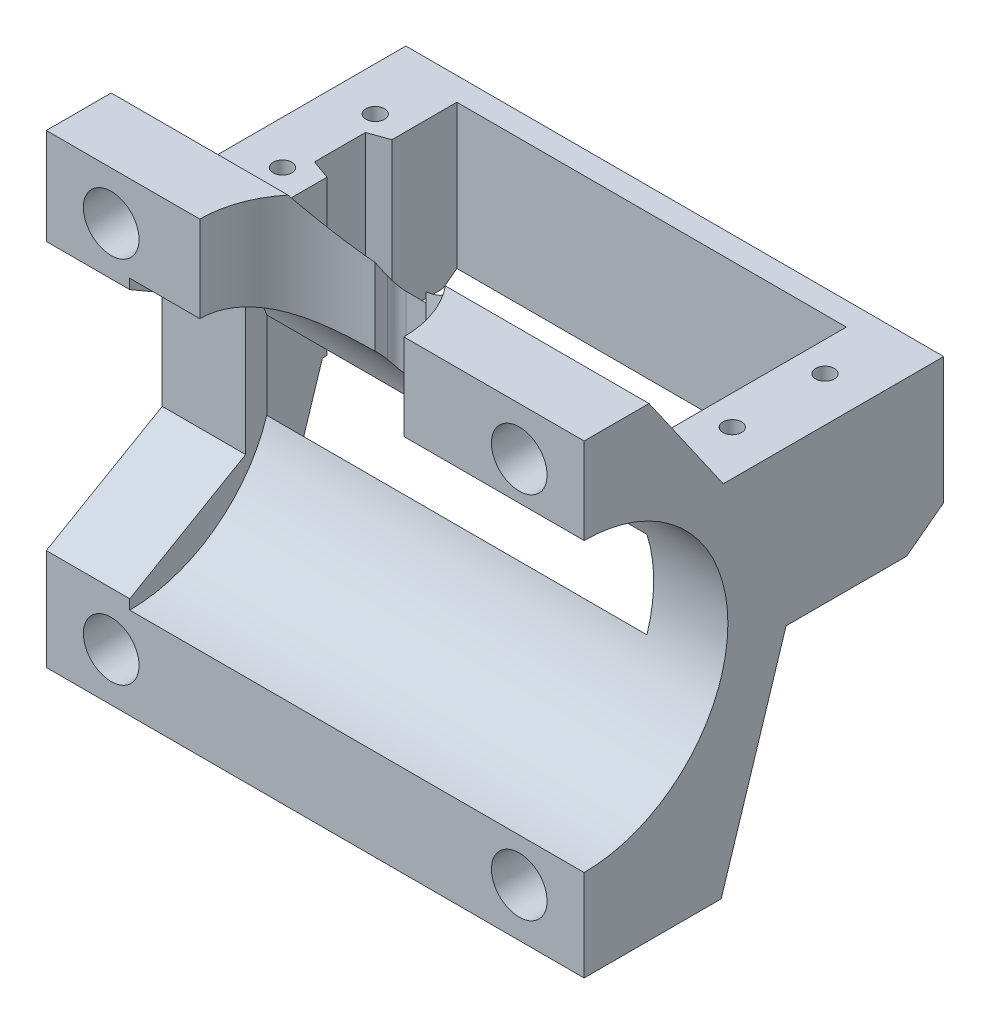
SolidWorks part; units mm, degrees
ref_plane "Front Plane" through (0, 0, 0) normal (0, 0, 1) x (1, 0, 0)
ref_plane "Top Plane" through (0, 0, 0) normal (0, 1, 0) x (1, 0, 0)
ref_plane "Right Plane" through (0, 0, 0) normal (1, 0, 0) x (0, 0, -1)
ref_plane "Plane1" through (0, -30, 0) normal (0, 1, 0) x (1, 0, 0)
sketch "Sketch1" plane through (0, -30, 0) normal (0, 1, 0) x (1, 0, 0)
  line L0 (-4.2598, -25.7738) -> (4.15, -25.7738) construction
  line L1 (29, -25.7738) -> (-29, -25.7738)
  line L2 (29, -25.7738) -> (29, 13)
  line L3 (29, 13) -> (-29, 13)
  line L4 (-29, -25.7738) -> (-29, 13)
  line L5 (29, -25.7738) -> (-29, 13) construction
  line L6 (29, 13) -> (-29, -25.7738) construction
  line L8 (27, 3.8) -> (27, -3.8) construction
  line L9 (-8.46, 10) -> (19.75, 10) construction
  line L10 (-27, -3.8) -> (-27, 3.8) construction
  line L12 (21, 10.5) -> (-21, 10.5)
  line L13 (21, 10.5) -> (21, -11)
  line L14 (21, -11) -> (-21, -11)
  line L15 (-21, 10.5) -> (-21, -11)
  point P0 (0, -6.3869)
  point P9 (-0.0549, -25.7738)
  dimension "D1" = 2
  dimension "D2" = 2.5
  dimension "D3" = 2
  dimension "D4" = 3
  dimension "D5" = 8
  dimension "D6" = 8
  dimension "D7" = 21.5
extrude "Boss-Extrude2" add sketch "Sketch1" along normal up to surface (38.65 mm away)
sketch "Sketch6" plane through (29, 0, 0) normal (1, 0, 0) x (0, 0, -1)
  line L0 (-11, -30) -> (-4, -8)
  line L1 (-25.7738, -30) -> (13, -30) construction
  line L2 (-4, -8) -> (9, -8)
  line L3 (9, -8) -> (13, -5)
  line L4 (13, 8.65) -> (13, -30) construction
  line L5 (13, -5) -> (13, -30)
  line L6 (13, -30) -> (-11, -30)
  dimension "D1" = 24
  dimension "D2" = 17
  dimension "D3" = 22
  dimension "D4" = 3
  dimension "D5" = 4
extrude "Cut-Extrude3" cut sketch "Sketch6" against normal through all
sketch "Sketch7" plane through (0, -8, 0) normal (0, -1, 0) x (1, 0, 0)
  line L0 (-21, -9) -> (-21, 4) construction
  line L1 (-21, -9) -> (-29, -9)
  line L2 (-21, -9) -> (-21, 4)
  line L3 (-21, 4) -> (-29, 4)
  line L4 (-29, -9) -> (-29, 4)
  line L5 (-29, 4) -> (-29, 11) construction
  line L6 (-29, -9) -> (-21, -9) construction
  line L7 (-29, 4) -> (-21, 4) construction
extrude "Cut-Extrude4" [suppressed] cut sketch "Sketch7" against normal blind 8
sketch "Sketch8" plane through (-29, 0, 0) normal (-1, 0, 0) x (0, 0, 1)
  line L0 (25.7738, 8.65) -> (25.7738, -30) construction
  line L1 (25.7738, 9.7838) -> (13.2738, 2.5669)
  line L2 (13.2738, 2.5669) -> (13.2738, -11.8669)
  line L3 (13.2738, -11.8669) -> (25.7738, -19.0838)
  line L4 (25.7738, -19.0838) -> (38.2738, -11.8669)
  line L5 (38.2738, -11.8669) -> (38.2738, 2.5669)
  line L6 (38.2738, 2.5669) -> (25.7738, 9.7838)
  circle A0 centre (25.7738, -4.65) radius 12.5 construction
  dimension "D1" = 12.5
sketch "Sketch9" plane through (-29, 0, 0) normal (-1, 0, 0) x (0, 0, 1)
  line L0 (10.7738, 8.65) -> (18.7738, 20.15)
  line L1 (25.7738, 8.65) -> (-13, 8.65) construction
  line L2 (18.7738, 20.15) -> (25.7738, 20.15)
  line L3 (25.7738, 20.15) -> (25.7738, 8.65)
  line L4 (10.7738, 8.65) -> (25.7738, 8.65)
  dimension "D1" = 7
  dimension "D2" = 11.5
  dimension "D3" = 15
extrude "Boss-Extrude3" add sketch "Sketch9" against normal up to surface (58 mm away) up to face at (29, -9.1, 4.5068)
extrude "Cut-Extrude5" cut sketch "Sketch8" against normal through all
sketch "Sketch10" plane through (0, 20.15, 0) normal (0, 1, 0) x (1, 0, 0)
  line L0 (29, -25.7738) -> (-29, -25.7738) construction
  line L1 (-4.2, -25.7738) -> (1.3, -25.7738)
  line L2 (-4.2, -25.7738) -> (-4.2, -12.7738)
  line L3 (-4.2, -12.7738) -> (1.3, -12.7738)
  line L4 (1.3, -25.7738) -> (1.3, -12.7738)
  circle A0 centre (-1.45, -25.7738) radius 11
  arc A1 (-7.95, -25.7738) -> (5.05, -25.7738) centre (-1.45, -25.7738) ccw construction
  point P11 (-1.45, -12.7738)
  line M7 (29, -18.7738) -> (-29, -18.7738)
  line M9 (-29, -25.7738) -> (29, -25.7738)
  dimension "D1" = 22
  dimension "D2" = 5.5
  dimension "D3" = 13
extrude "Cut-Extrude6" cut sketch "Sketch10" against normal blind 17 contours A0 L4 L3 L2 | A0 L4 M9 M7 | A0 L4 M7 | L4 A0 L2 M7 | A0 L2 M7 M9 | L4 L2 M9 M7 | L2 A0 M7
fillet "Fillet1" radius 1 2 edges at (1.3, 7.3375, 12.7738) (-4.2, 7.3375, 12.7738)
sketch "Sketch11" plane through (0, 0, 0) normal (1, 0, 0) x (0, 0, -1)
  circle A0 centre (-25.7738, -4.65) radius 15.5
  dimension "D1" = 31
extrude "Cut-Extrude7" cut sketch "Sketch11" against normal blind 20 and the other way through all contours A0
sketch "Sketch12" plane through (0, 0, 25.7738) normal (0, 0, 1) x (1, 0, 0)
  line L0 (-29, -4.925) -> (29, -4.925) construction
  line L1 (-29, 20.15) -> (-29, 9.7838) construction
  line L2 (29, 20.15) -> (29, 10.85) construction
  line L3 (-29, -30) -> (29, -30) construction
  line L4 (29, 20.15) -> (9.55, 20.15) construction
  circle A0 centre (-22, 14.9669) radius 3
  circle A1 centre (22, 14.9669) radius 3
  circle A2 centre (22, -24.8169) radius 3
  circle A3 centre (-22, -24.8169) radius 3
  point P14 (-29, 14.9669)
  dimension "D1" = 6
  dimension "D2" = 7
  dimension "D3" = 7
extrude "Cut-Extrude8" cut sketch "Sketch12" against normal blind 20
sketch "Sketch13" plane through (0, 0, 0) normal (0, 0, 1) x (1, 0, 0)
  line L0 (-29, -4.925) -> (29, -4.925) construction
  line L1 (29, 8.65) -> (29, -5) construction
  line L2 (-29, 8.65) -> (-29, -5) construction
  line L3 (29, 20.15) -> (7.0353, 20.15) construction
  line L4 (-21, -30) -> (21, -30) construction
  circle A0 centre (22, 14.9669) radius 4
  circle A1 centre (-22, 14.9669) radius 4
  circle A2 centre (22, -24.8169) radius 4
  circle A3 centre (-22, -24.8169) radius 4
  dimension "D1" = 8
extrude "Cut-Extrude9" cut sketch "Sketch13" along normal blind 20
sketch "Sketch15" plane through (0, 8.65, 0) normal (0, 1, 0) x (1, 0, 0)
  line L0 (29, 13) -> (29, -10.7738) construction
  line L1 (-29, 0) -> (29, 0) construction
  line L2 (-29, -10.7738) -> (-29, 13) construction
  circle A0 centre (-24.3, 5) radius 1
  circle A1 centre (-24.3, -5) radius 1
  circle A2 centre (24.2, 5) radius 1
  circle A3 centre (24.2, -5) radius 1
  dimension "D1" = 2
  dimension "D2" = 2
  dimension "D3" = 48.5
extrude "Cut-Extrude10" cut sketch "Sketch15" against normal blind 10
sketch "Sketch17" plane through (0, 8.65, 0) normal (0, 1, 0) x (1, 0, 0)
  line L5 (-21, 0) -> (-23.1, 0) construction
  line L6 (-21, -10.7738) -> (-21, 10.5) construction
  line L7 (-21, -3.5) -> (-21, 3.5)
  line L8 (-21, 3.5) -> (-23.1, 2.75)
  line L9 (-23.1, 2.75) -> (-23.1, -2.75)
  line L10 (-21, -3.5) -> (-23.1, -2.75)
  dimension "D1" = 7
  dimension "D2" = 5.5
  dimension "D3" = 2.1
extrude "Cut-Extrude11" cut sketch "Sketch17" against normal through all
